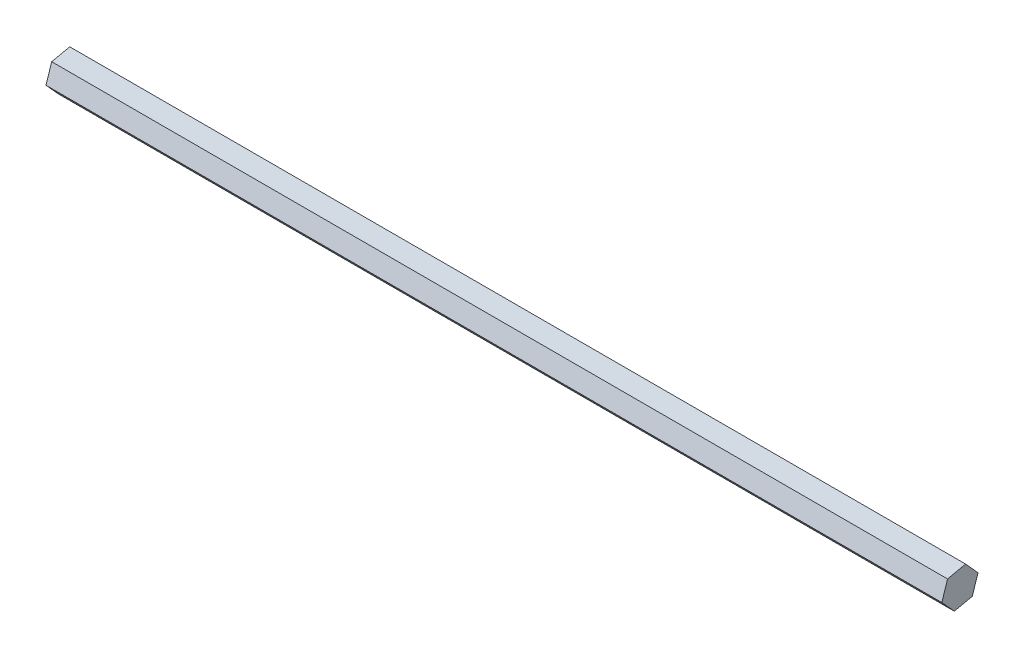
SolidWorks part; units mm, degrees
material "7075-T6 (SN)"
ref_plane "Front Plane" through (0, 0, 0) normal (0, 0, 1) x (1, 0, 0)
ref_plane "Top Plane" through (0, 0, 0) normal (0, 1, 0) x (1, 0, 0)
ref_plane "Right Plane" through (0, 0, 0) normal (1, 0, 0) x (0, 0, -1)
sketch "Sketch1" plane through (0, 0, 0) normal (1, 0, 0) x (0, 0, -1)
  line L1 (-27.7852, -21.36) -> (-20.6155, -19.8242)
  line L2 (-20.6155, -19.8242) -> (-18.3606, -12.8472)
  line L3 (-18.3606, -12.8472) -> (-23.2755, -7.4059)
  line L4 (-23.2755, -7.4059) -> (-30.4452, -8.9416)
  line L5 (-30.4452, -8.9416) -> (-32.7001, -15.9187)
  line L6 (-32.7001, -15.9187) -> (-27.7852, -21.36)
  circle A0 centre (-25.5304, -14.3829) radius 6.35 construction
  dimension "D1" = 12.7
extrude "Boss-Extrude1" add sketch "Sketch1" along normal blind 177.8 and the other way blind 177.8
sketch "Sketch2" plane through (177.8, 0, 0) normal (1, 0, 0) x (0, 0, -1)
  line L0 (-32.7001, -15.9187) -> (-18.3606, -12.8472) construction
  line L1 (-30.4452, -8.9416) -> (-32.7001, -15.9187) construction
  line L2 (-27.7852, -21.36) -> (-20.6155, -19.8242) construction
  line L3 (-24.2004, -20.5921) -> (-26.8603, -8.1738) construction
  line L4 (-23.2755, -7.4059) -> (-30.4452, -8.9416) construction
  circle A0 centre (-25.5304, -14.3829) radius 6.35
  point P4 (-25.5304, -14.3829)
